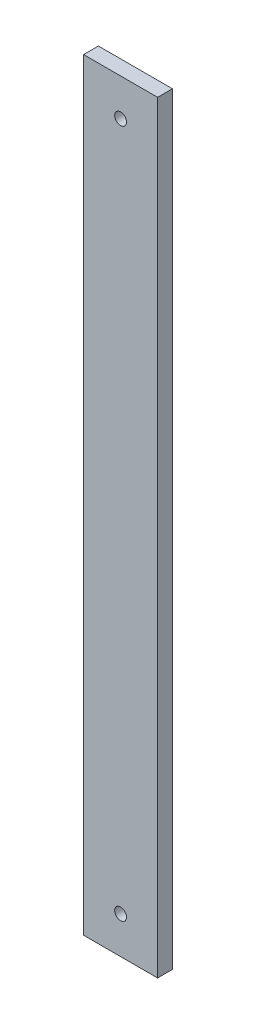
SolidWorks part; units mm, degrees
material "A-玻璃纤维"
ref_plane "前视基准面" through (0, 0, 0) normal (0, 0, 1) x (1, 0, 0)
ref_plane "上视基准面" through (0, 0, 0) normal (0, 1, 0) x (1, 0, 0)
ref_plane "右视基准面" through (0, 0, 0) normal (1, 0, 0) x (0, 0, -1)
sketch "草图1" plane through (0, 0, 0) normal (0, 0, 1) x (1, 0, 0)
  line L1 (-10, 103) -> (10, 103)
  line L2 (-10, 103) -> (-10, -103)
  line L3 (-10, -103) -> (10, -103)
  line L4 (10, 103) -> (10, -103)
  line L5 (0, -103) -> (0, 103) construction
  line L6 (-10, 0) -> (10, 0) construction
  circle A0 centre (0, 93) radius 1.6
  circle A1 centre (0, -93) radius 1.6
  point P0 (0, 0)
  dimension "D3" = 3.2
  dimension "D1" = 206
  dimension "D2" = 20
  dimension "D4" = 186
extrude "凸台-拉伸1" add sketch "草图1" along normal blind 4
